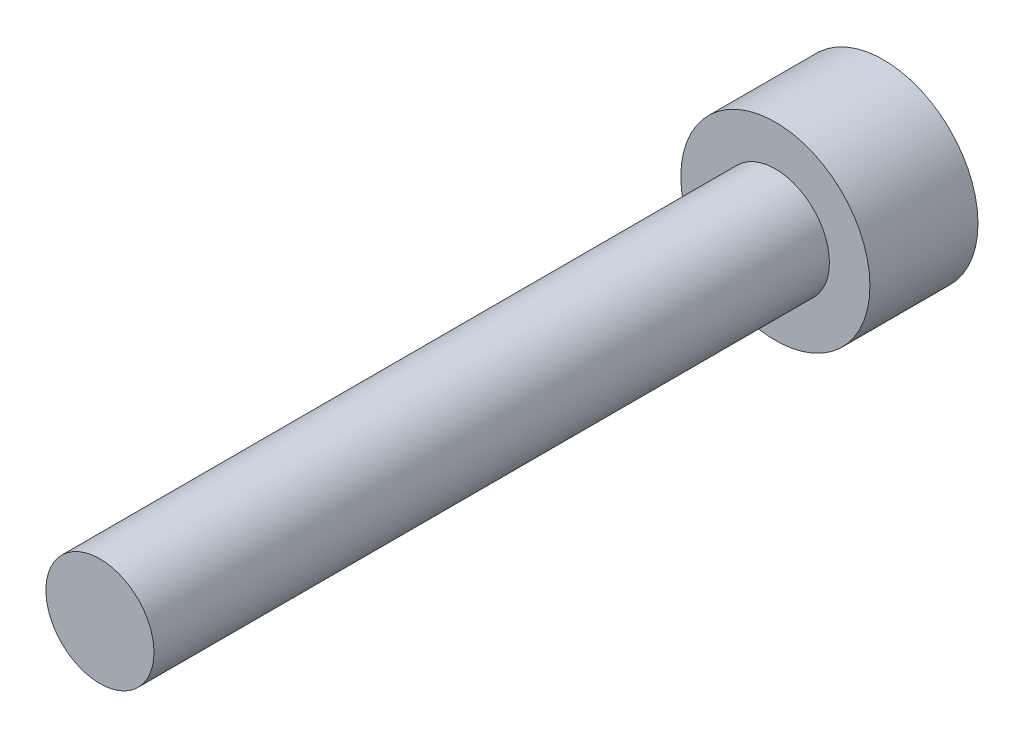
SolidWorks part; units mm, degrees
ref_plane "前视基准面" through (0, 0, 0) normal (0, 0, 1) x (1, 0, 0)
ref_plane "上视基准面" through (0, 0, 0) normal (0, 1, 0) x (1, 0, 0)
ref_plane "右视基准面" through (0, 0, 0) normal (1, 0, 0) x (0, 0, -1)
sketch "草图1" plane through (0, 0, 0) normal (0, 0, 1) x (1, 0, 0)
  circle A0 centre (0, 0) radius 2
  dimension "D1" = 4
extrude "金属件无牙型包络" add sketch "草图1" along normal blind 25
sketch "草图2" plane through (0, 0, 0) normal (0, 0, 1) x (1, 0, 0)
  circle A0 centre (0, 0) radius 3.5
  dimension "D1" = 7
extrude "标准件头部包络" add sketch "草图2" along normal blind 4 from offset 4
